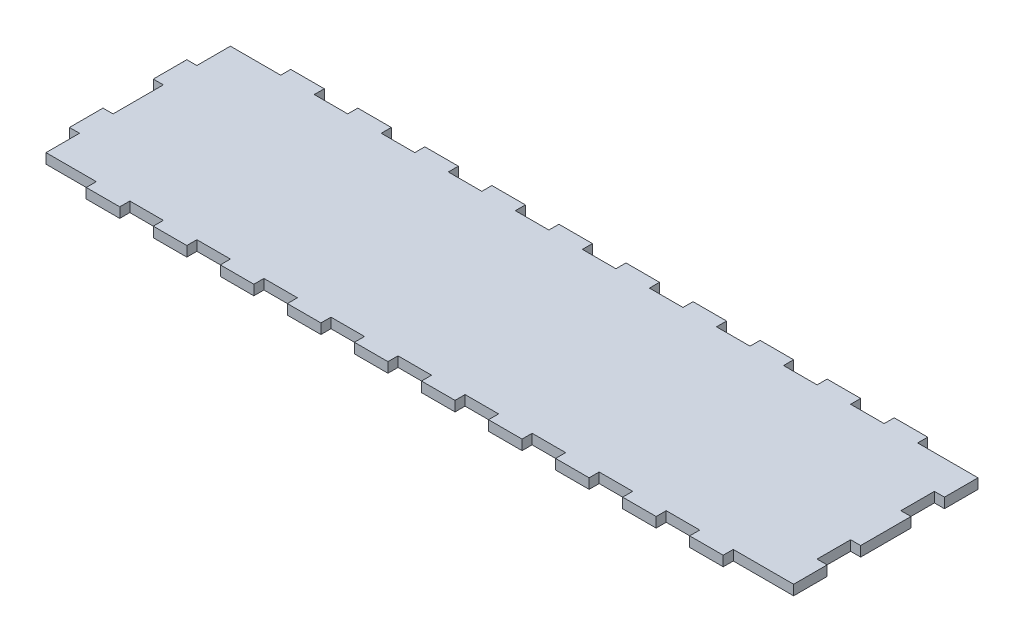
SolidWorks part; units mm, degrees
ref_plane "Спереди" through (0, 0, 0) normal (0, 0, 1) x (1, 0, 0)
ref_plane "Сверху" through (0, 0, 0) normal (0, 1, 0) x (1, 0, 0)
ref_plane "Справа" through (0, 0, 0) normal (1, 0, 0) x (0, 0, -1)
sketch "Эскиз3" plane through (0, 0, 0) normal (0, 1, 0) x (1, 0, 0)
  line L0 (0, 0) -> (0, 9.4426) construction
  line L1 (0, 0) -> (18.7316, 0) construction
  line L2 (-75, 27.5) -> (-75, 30.5)
  line L3 (-15, -27.5) -> (-25, -27.5)
  line L4 (-35, -27.5) -> (-45, -27.5)
  line L5 (5, 27.5) -> (-5, 27.5)
  line L6 (-110, -7.5) -> (-110, 7.5)
  line L7 (-110, 17.5) -> (-113, 17.5)
  line L8 (-95, 27.5) -> (-110, 27.5)
  line L9 (-110, 7.5) -> (-113, 7.5)
  line L10 (-113, 17.5) -> (-113, 7.5)
  line L11 (-75, 27.5) -> (-85, 27.5)
  line L12 (-95, 27.5) -> (-95, 30.5)
  line L13 (-95, 30.5) -> (-85, 30.5)
  line L14 (-85, 27.5) -> (-85, 30.5)
  line L15 (-75, 30.5) -> (-65, 30.5)
  line L16 (-65, 27.5) -> (-65, 30.5)
  line L17 (-55, 27.5) -> (-55, 30.5)
  line L18 (-55, 30.5) -> (-45, 30.5)
  line L19 (-45, 27.5) -> (-45, 30.5)
  line L20 (-35, 27.5) -> (-35, 30.5)
  line L21 (-35, 30.5) -> (-25, 30.5)
  line L22 (-25, 27.5) -> (-25, 30.5)
  line L23 (-15, 27.5) -> (-15, 30.5)
  line L24 (-15, 30.5) -> (-5, 30.5)
  line L25 (-5, 27.5) -> (-5, 30.5)
  line L26 (-110, 17.5) -> (-110, 27.5)
  line L27 (-55, 27.5) -> (-65, 27.5)
  line L28 (-35, 27.5) -> (-45, 27.5)
  line L29 (-15, 27.5) -> (-25, 27.5)
  line L30 (-55, -27.5) -> (-65, -27.5)
  line L31 (-110, -17.5) -> (-110, -27.5)
  line L32 (-5, -27.5) -> (-5, -30.5)
  line L33 (-15, -30.5) -> (-5, -30.5)
  line L34 (-15, -27.5) -> (-15, -30.5)
  line L35 (-25, -27.5) -> (-25, -30.5)
  line L36 (-35, -30.5) -> (-25, -30.5)
  line L37 (-35, -27.5) -> (-35, -30.5)
  line L38 (-45, -27.5) -> (-45, -30.5)
  line L39 (-55, -30.5) -> (-45, -30.5)
  line L40 (-55, -27.5) -> (-55, -30.5)
  line L41 (-65, -27.5) -> (-65, -30.5)
  line L42 (-75, -30.5) -> (-65, -30.5)
  line L43 (-85, -27.5) -> (-85, -30.5)
  line L44 (-95, -30.5) -> (-85, -30.5)
  line L45 (-95, -27.5) -> (-95, -30.5)
  line L46 (-75, -27.5) -> (-85, -27.5)
  line L47 (-113, -17.5) -> (-113, -7.5)
  line L48 (-110, -7.5) -> (-113, -7.5)
  line L49 (-95, -27.5) -> (-110, -27.5)
  line L50 (-110, -17.5) -> (-113, -17.5)
  line L51 (5, -27.5) -> (-5, -27.5)
  line L52 (-75, -27.5) -> (-75, -30.5)
  line L53 (75, -27.5) -> (75, -30.5)
  line L54 (110, -17.5) -> (113, -17.5)
  line L55 (95, -27.5) -> (110, -27.5)
  line L56 (110, -7.5) -> (113, -7.5)
  line L58 (75, -27.5) -> (85, -27.5)
  line L59 (95, -27.5) -> (95, -30.5)
  line L60 (95, -30.5) -> (85, -30.5)
  line L61 (85, -27.5) -> (85, -30.5)
  line L62 (75, -30.5) -> (65, -30.5)
  line L63 (65, -27.5) -> (65, -30.5)
  line L64 (55, -27.5) -> (55, -30.5)
  line L65 (55, -30.5) -> (45, -30.5)
  line L66 (45, -27.5) -> (45, -30.5)
  line L67 (35, -27.5) -> (35, -30.5)
  line L68 (35, -30.5) -> (25, -30.5)
  line L69 (25, -27.5) -> (25, -30.5)
  line L70 (15, -27.5) -> (15, -30.5)
  line L71 (15, -30.5) -> (5, -30.5)
  line L72 (5, -27.5) -> (5, -30.5)
  line L74 (55, -27.5) -> (65, -27.5)
  line L75 (15, 27.5) -> (25, 27.5)
  line L76 (35, 27.5) -> (45, 27.5)
  line L77 (55, 27.5) -> (65, 27.5)
  line L79 (5, 27.5) -> (5, 30.5)
  line L80 (15, 30.5) -> (5, 30.5)
  line L81 (15, 27.5) -> (15, 30.5)
  line L82 (25, 27.5) -> (25, 30.5)
  line L83 (35, 30.5) -> (25, 30.5)
  line L84 (35, 27.5) -> (35, 30.5)
  line L85 (45, 27.5) -> (45, 30.5)
  line L86 (55, 30.5) -> (45, 30.5)
  line L87 (55, 27.5) -> (55, 30.5)
  line L88 (65, 27.5) -> (65, 30.5)
  line L89 (75, 30.5) -> (65, 30.5)
  line L90 (85, 27.5) -> (85, 30.5)
  line L91 (95, 30.5) -> (85, 30.5)
  line L92 (95, 27.5) -> (95, 30.5)
  line L93 (75, 27.5) -> (85, 27.5)
  line L95 (110, 7.5) -> (113, 7.5)
  line L96 (95, 27.5) -> (110, 27.5)
  line L97 (110, 17.5) -> (113, 17.5)
  line L99 (35, -27.5) -> (45, -27.5)
  line L100 (15, -27.5) -> (25, -27.5)
  line L101 (75, 27.5) -> (75, 30.5)
  line L102 (110, 27.5) -> (113, 27.5)
  line L103 (113, 27.5) -> (113, 17.5)
  line L104 (110, 17.5) -> (110, 7.5)
  line L105 (113, 7.5) -> (113, -7.5)
  line L106 (110, -7.5) -> (110, -17.5)
  line L107 (113, -17.5) -> (113, -27.5)
  line L108 (113, -27.5) -> (110, -27.5)
  point P4 (110, 0)
  point P55 (-110, 0)
  point P59 (0, -27.5)
  point P106 (0, 27.5)
  dimension "D6" = 10
  dimension "D1" = 110
  dimension "D2" = 27.5
  dimension "D3" = 10
  dimension "D4" = 3
  dimension "D5" = 7.5
  dimension "D7" = 3
  dimension "D8" = 15
  dimension "D9" = 5
extrude "Бобышка-Вытянуть2" add sketch "Эскиз3" along normal blind 3
